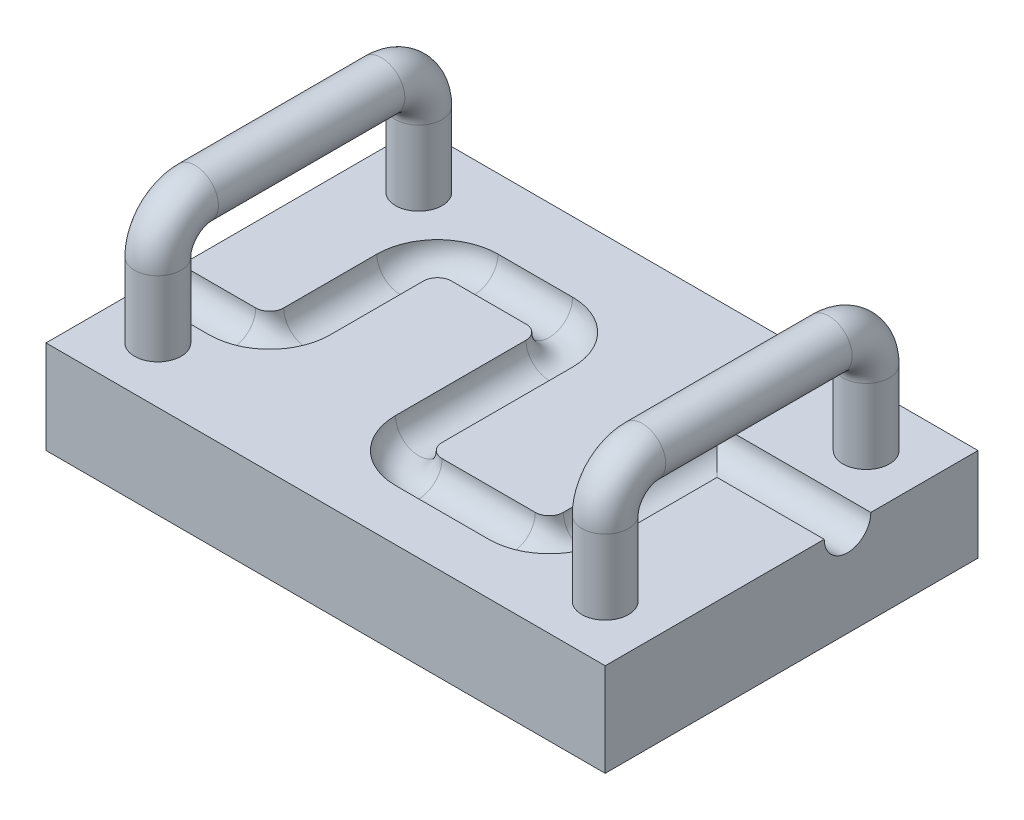
SolidWorks part; units mm, degrees
ref_plane "Front Plane" through (0, 0, 0) normal (0, 0, 1) x (1, 0, 0)
ref_plane "Top Plane" through (0, 0, 0) normal (0, 1, 0) x (1, 0, 0)
ref_plane "Right Plane" through (0, 0, 0) normal (1, 0, 0) x (0, 0, -1)
sketch "Sketch1" plane through (0, 0, 0) normal (0, 1, 0) x (1, 0, 0)
  line L1 (150, -100) -> (-150, -100)
  line L2 (150, -100) -> (150, 100)
  line L3 (150, 100) -> (-150, 100)
  line L4 (-150, -100) -> (-150, 100)
  line L5 (150, -100) -> (-150, 100) construction
  line L6 (150, 100) -> (-150, -100) construction
  point P0 (0, 0)
  dimension "D1" = 200
  dimension "D2" = 300
extrude "Boss-Extrude1" add sketch "Sketch1" against normal blind 50
sketch "Sketch2" plane through (0, 0, 0) normal (0, 1, 0) x (1, 0, 0)
  line L0 (-150, -40) -> (-110, -40)
  line L1 (-150, 100) -> (-150, -100) construction
  line L2 (-90, -20) -> (-90, 30)
  line L3 (-70, 50) -> (-30, 50)
  line L4 (-10, 30) -> (-10, -40)
  line L5 (10, -60) -> (60, -60)
  line L6 (80, -40) -> (80, 30)
  line L7 (80, 30) -> (150, 30)
  line L8 (150, -100) -> (150, 100) construction
  line L9 (-150, -100) -> (150, -100) construction
  arc A0 (60, -60) -> (80, -40) centre (60, -40) ccw
  arc A1 (-10, -40) -> (10, -60) centre (10, -40) ccw
  arc A2 (-30, 50) -> (-10, 30) centre (-30, 30) cw
  arc A3 (-90, 30) -> (-70, 50) centre (-70, 30) cw
  arc A4 (-110, -40) -> (-90, -20) centre (-110, -20) ccw
  point P16 (80, -60)
  point P19 (-10, -60)
  point P22 (-10, 50)
  point P25 (-90, 50)
  point P28 (-90, -40)
  dimension "D8" = 20
  dimension "D1" = 60
  dimension "D2" = 60
  dimension "D3" = 90
  dimension "D4" = 80
  dimension "D5" = 90
  dimension "D6" = 90
  dimension "D7" = 110
sweep "Cut-Sweep1" cut path "Sketch2" circular profile diameter 25 parameters "D3"=25
sketch "Sketch3" plane through (0, 0, 0) normal (0, 1, 0) x (1, 0, 0)
  line L0 (-150, 100) -> (-150, -27.5) construction
  line L1 (150, 100) -> (-150, 100) construction
  line L2 (-27.5, 0) -> (27.5, 0) construction
  circle A0 centre (-120, 70) radius 12.5
  circle A1 centre (-120, -70) radius 12.5
  dimension "D2" = 25
  dimension "D1" = 30
  dimension "D3" = 30
ref_plane "Plane1" through (-120, 0, 0) normal (-1, 0, 0) x (0, 0, 1)
sketch "Sketch4" plane through (-120, 0, 0) normal (-1, 0, 0) x (0, 0, 1)
  line L0 (-70, 0) -> (-70, 40)
  line L1 (-57.5, 0) -> (-82.5, 0) construction
  line L2 (-50, 60) -> (50, 60)
  line L3 (70, 40) -> (70, 0)
  line L4 (82.5, 0) -> (57.5, 0) construction
  arc A0 (-70, 40) -> (-50, 60) centre (-50, 40) cw
  arc A1 (50, 60) -> (70, 40) centre (50, 40) cw
  point P12 (70, 60)
  dimension "D2" = 20
  dimension "D1" = 60
sweep "Sweep1" add path "Sketch4" circular profile diameter 25 parameters "D3"=25
mirror "Mirror1" about plane through (0, 0, 0) normal (1, 0, 0) of "Sweep1"
